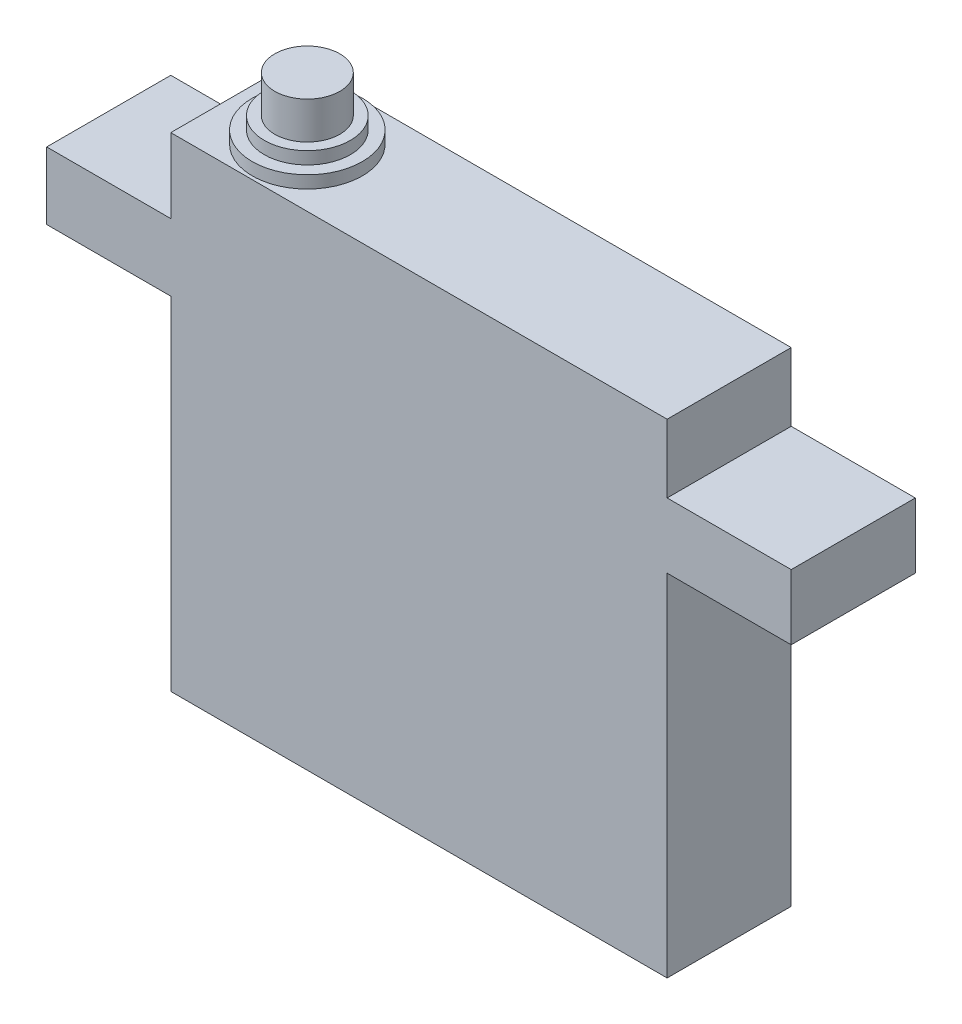
SolidWorks part; units mm, degrees
ref_plane "前视基准面" through (0, 0, 0) normal (0, 0, 1) x (1, 0, 0)
ref_plane "上视基准面" through (0, 0, 0) normal (0, 1, 0) x (1, 0, 0)
ref_plane "右视基准面" through (0, 0, 0) normal (1, 0, 0) x (0, 0, -1)
other "Configuration Table"
sketch "草图1" plane through (0, 0, 0) normal (0, 0, 1) x (1, 0, 0)
  line L1 (-32.526, -28.7985) -> (7.474, -28.7985)
  line L2 (-32.526, -28.7985) -> (-32.526, 10.2015)
  line L3 (-32.526, 10.2015) -> (7.474, 10.2015)
  line L4 (7.474, -28.7985) -> (7.474, 10.2015)
  line L5 (-32.526, -28.7985) -> (7.474, 10.2015) construction
  line L6 (-32.526, 10.2015) -> (7.474, -28.7985) construction
  point P0 (-12.526, -9.2985)
  dimension "D1" = 40
  dimension "D2" = 39
extrude "凸台-拉伸1" add sketch "草图1" along normal blind 10
sketch "草图2" plane through (0, 10.2015, 0) normal (0, 1, 0) x (1, 0, 0)
  circle A0 centre (-26.2163, -5.3061) radius 4.4327
  point P2 (0, 0)
extrude "凸台-拉伸4" add sketch "草图2" along normal blind 1 contours A0
sketch "草图3" plane through (0, 11.2015, 0) normal (0, 1, 0) x (1, 0, 0)
  circle A0 centre (-26.2163, -5.3061) radius 3.4694
extrude "凸台-拉伸5" add sketch "草图3" along normal blind 1 contours A0
sketch "草图5" plane through (0, 12.2015, 0) normal (0, 1, 0) x (1, 0, 0)
  circle A0 centre (-26.2163, -5.3061) radius 2.6209
extrude "凸台-拉伸6" add sketch "草图5" along normal blind 3
sketch "草图6" plane through (-32.526, 0, 0) normal (-1, 0, 0) x (0, 0, 1)
  line L0 (0, 10.2015) -> (0, -28.7985) construction
  line L1 (0, 4.2022) -> (10, 4.2022)
  line L2 (0, 4.2022) -> (0, -1.2144)
  line L3 (0, -1.2144) -> (10, -1.2144)
  line L4 (10, 4.2022) -> (10, -1.2144)
  line L5 (10, 10.2015) -> (10, -28.7985) construction
extrude "凸台-拉伸7" add sketch "草图6" along normal blind 10
sketch "草图7" plane through (7.474, 0, 0) normal (1, 0, 0) x (0, 0, -1)
  line L0 (-10, -28.7985) -> (-10, 10.2015) construction
  line L1 (-10, 4.7048) -> (0, 4.7048)
  line L2 (-10, 4.7048) -> (-10, -0.5443)
  line L3 (-10, -0.5443) -> (0, -0.5443)
  line L4 (0, 4.7048) -> (0, -0.5443)
  line L5 (0, -28.7985) -> (0, 10.2015) construction
extrude "凸台-拉伸8" add sketch "草图7" along normal blind 10
sketch "草图8" plane through (0, 4.7048, 0) normal (0, 1, 0) x (1, 0, 0)
  circle A0 centre (12.2818, -2.9791) radius 1.9506
  circle A1 centre (12.2818, -7.5261) radius 1.8315
  circle A2 centre (-37.6726, -2.5261) radius 2.1022
  circle A3 centre (-37.6726, -7.5261) radius 1.8062
  point P8 (0, 0)
  point P9 (0, 0)
  point P10 (12.2818, -2.9791)
  point P11 (0, 0)
  dimension "D2" = 3.9012
  dimension "D1" = 5
